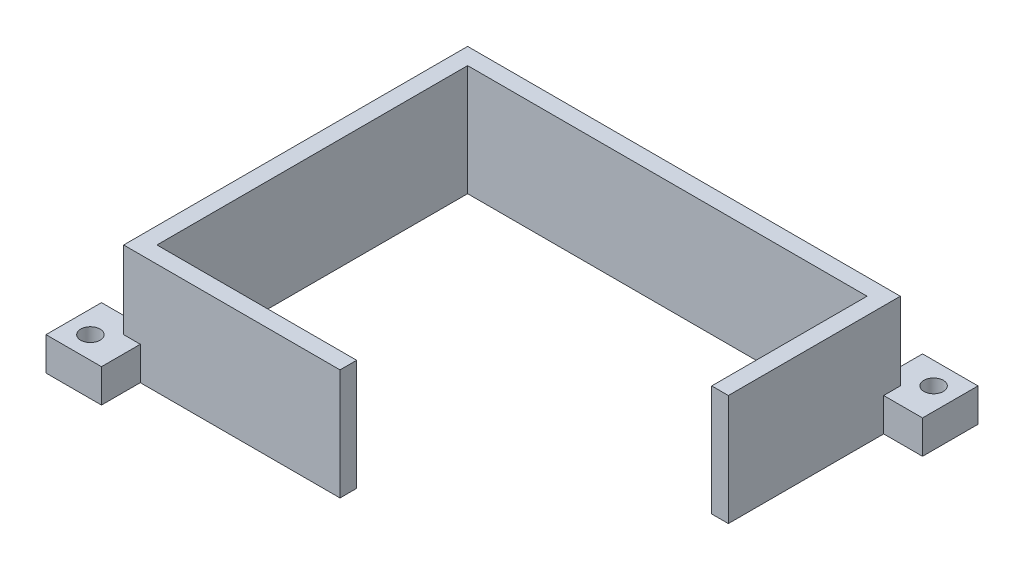
SolidWorks part; units mm, degrees
ref_plane "前视基准面" through (0, 0, 0) normal (0, 0, 1) x (1, 0, 0)
ref_plane "上视基准面" through (0, 0, 0) normal (0, 1, 0) x (1, 0, 0)
ref_plane "右视基准面" through (0, 0, 0) normal (1, 0, 0) x (0, 0, -1)
sketch "草图1" plane through (0, 0, 0) normal (0, 1, 0) x (1, 0, 0)
  line L0 (0, -28) -> (0, -31)
  line L1 (-36, 28) -> (36, 28)
  line L2 (-36, 28) -> (-36, -28)
  line L3 (-36, -28) -> (0, -28)
  line L4 (36, 28) -> (36, 0)
  line L5 (-36, 28) -> (36, -28) construction
  line L6 (-36, -28) -> (36, 28) construction
  line L7 (0, -31) -> (-39, -31)
  line L8 (-39, -31) -> (-39, 31)
  line L9 (-39, 31) -> (39, 31)
  line L10 (39, 31) -> (39, 0)
  line L11 (39, 0) -> (36, 0)
  line L12 (0, -28) -> (36, -28) construction
  line L13 (36, 0) -> (36, -28) construction
  point P0 (0, 0)
  dimension "D1" = 72
  dimension "D2" = 56
  dimension "D3" = 3
  dimension "D4" = 3
  dimension "D5" = 3
  dimension "D6" = 3
extrude "凸台-拉伸1" add sketch "草图1" along normal blind 20
sketch "草图2" plane through (0, 0, 0) normal (0, -1, 0) x (1, 0, 0)
  line L0 (-8.6165, 0) -> (13.9811, 0) construction
  line L1 (-36, 28) -> (-46, 28)
  line L2 (-36, 28) -> (-36, 38)
  line L3 (-36, 38) -> (-46, 38)
  line L4 (-46, 28) -> (-46, 38)
  line L13 (-46, -28) -> (-46, -38)
  line L14 (-36, -38) -> (-46, -38)
  line L15 (-36, -28) -> (-36, -38)
  line L16 (-36, -28) -> (-46, -28)
  line L17 (0, 12.1031) -> (0, -14.0315) construction
  line L18 (36, -28) -> (46, -28)
  line L19 (36, -28) -> (36, -38)
  line L20 (36, -38) -> (46, -38)
  line L21 (46, -28) -> (46, -38)
  circle A0 centre (-42, 34) radius 1.75
  circle A1 centre (-42, -34) radius 1.75
  circle A2 centre (42, -34) radius 1.75
  dimension "D7" = 3.5
  dimension "D1" = 10
  dimension "D2" = 10
  dimension "D8" = 4
  dimension "D9" = 4
extrude "凸台-拉伸2" add sketch "草图2" against normal blind 6
